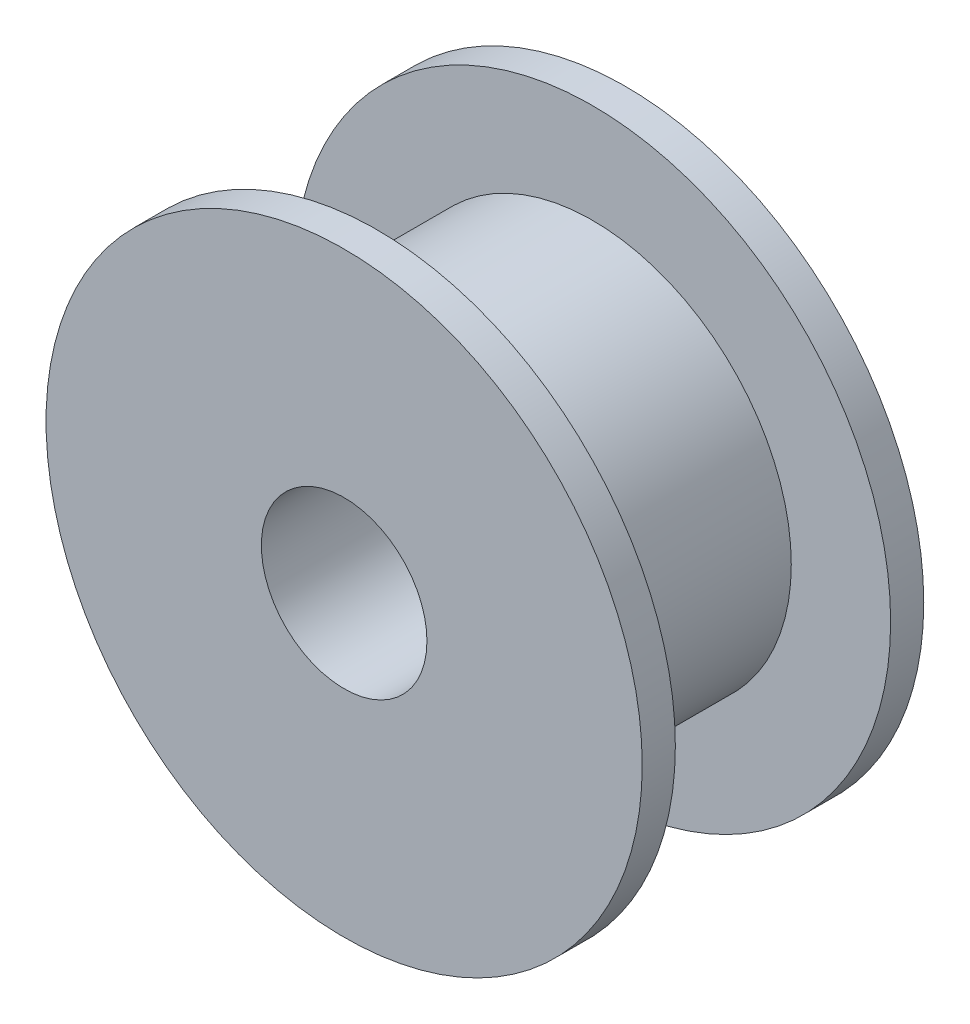
SolidWorks part; units mm, degrees
ref_plane "Front Plane" through (0, 0, 0) normal (0, 0, 1) x (1, 0, 0)
ref_plane "Top Plane" through (0, 0, 0) normal (0, 1, 0) x (1, 0, 0)
ref_plane "Right Plane" through (0, 0, 0) normal (1, 0, 0) x (0, 0, -1)
sketch "Sketch1" plane through (0, 0, 0) normal (0, 1, 0) x (1, 0, 0)
  line L1 (9, 0) -> (9, 1)
  line L2 (9, 1) -> (6, 1)
  line L3 (6, 1) -> (6, 7.5)
  line L4 (6, 7.5) -> (9, 7.5)
  line L5 (9, 7.5) -> (9, 8.5)
  line L8 (9, 8.5) -> (2.5, 8.5)
  line L9 (2.5, 8.5) -> (2.5, 0)
  line L10 (2.5, 0) -> (9, 0)
  line L11 (0, 0) -> (0, 9.6778) construction
  dimension "D1" = 9
  dimension "D2" = 6
  dimension "D3" = 2.5
  dimension "D4" = 6.5
  dimension "D5" = 8.5
revolve "Revolve1" add sketch "Sketch1" angle 360 about L11
